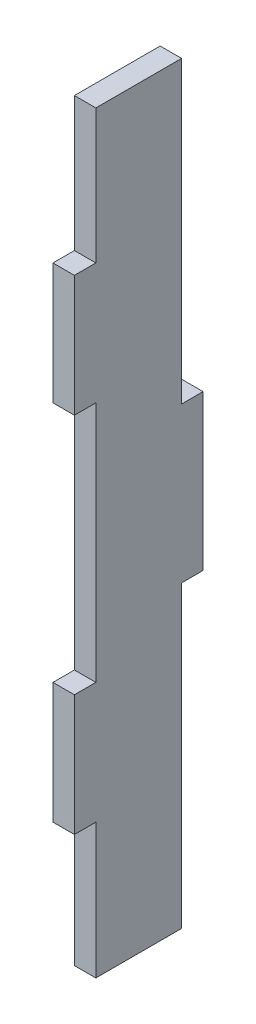
SolidWorks part; units mm, degrees
ref_plane "Front Plane" through (0, 0, 0) normal (0, 0, 1) x (1, 0, 0)
ref_plane "Top Plane" through (0, 0, 0) normal (0, 1, 0) x (1, 0, 0)
ref_plane "Right Plane" through (0, 0, 0) normal (1, 0, 0) x (0, 0, -1)
sketch "Sketch1" plane through (0, 0, 0) normal (1, 0, 0) x (0, 0, -1)
  line L1 (-9, 52.7) -> (9, 52.7)
  line L2 (-9, 52.7) -> (-9, -52.7)
  line L3 (-9, -52.7) -> (9, -52.7)
  line L4 (9, 52.7) -> (9, -52.7)
  line L5 (-9, 52.7) -> (9, -52.7) construction
  line L6 (-9, -52.7) -> (9, 52.7) construction
  point P0 (0, 0)
  dimension "D1" = 105.4
  dimension "D2" = 18
extrude "Boss-Extrude1" add sketch "Sketch1" along normal blind 3
sketch "Sketch3" plane through (3, 0, 0) normal (1, 0, 0) x (0, 0, -1)
  line L1 (9, -52.7) -> (6, -52.7)
  line L2 (9, -52.7) -> (9, -10.835)
  line L3 (9, -10.835) -> (6, -10.835)
  line L4 (6, -52.7) -> (6, -10.835)
  line L5 (9, 52.7) -> (6, 52.7)
  line L6 (9, 52.7) -> (9, 10.835)
  line L7 (9, 10.835) -> (6, 10.835)
  line L8 (6, 52.7) -> (6, 10.835)
  dimension "D1" = 3
  dimension "D2" = 3
  dimension "D3" = 41.865
  dimension "D4" = 41.865
extrude "Cut-Extrude2" cut sketch "Sketch3" against normal blind 3
sketch "Sketch5" plane through (0, 0, 0) normal (-1, 0, 0) x (0, 0, 1)
  line L0 (6, -16.89) -> (6, 16.97)
  line L1 (9, -52.7) -> (6, -52.7)
  line L2 (9, -52.7) -> (9, -33.82)
  line L3 (9, -33.82) -> (6, -33.82)
  line L4 (6, -52.7) -> (6, -33.82)
  line L5 (9, 52.7) -> (6, 52.7)
  line L6 (9, 52.7) -> (9, 33.92)
  line L7 (9, 33.92) -> (6, 33.92)
  line L8 (6, 52.7) -> (6, 33.92)
  line L9 (6, -16.89) -> (9, -16.89)
  line L10 (9, 52.7) -> (9, -52.7) construction
  line L11 (6, 16.97) -> (9, 16.97)
  line M10 (-6, -52.7) -> (9, -52.7)
  line M11 (9, -52.7) -> (9, 52.7)
  line M12 (9, 52.7) -> (-6, 52.7)
  dimension "D1" = 3
  dimension "D2" = 3
  dimension "D3" = 18.78
  dimension "D4" = 18.88
  dimension "D5" = 33.86
  dimension "D6" = 16.93
extrude "Cut-Extrude5" cut sketch "Sketch5" against normal blind 3 contours L4 L3 M10 M11 | L11 L0 L9 M11 | L8 L7 M12 M11
